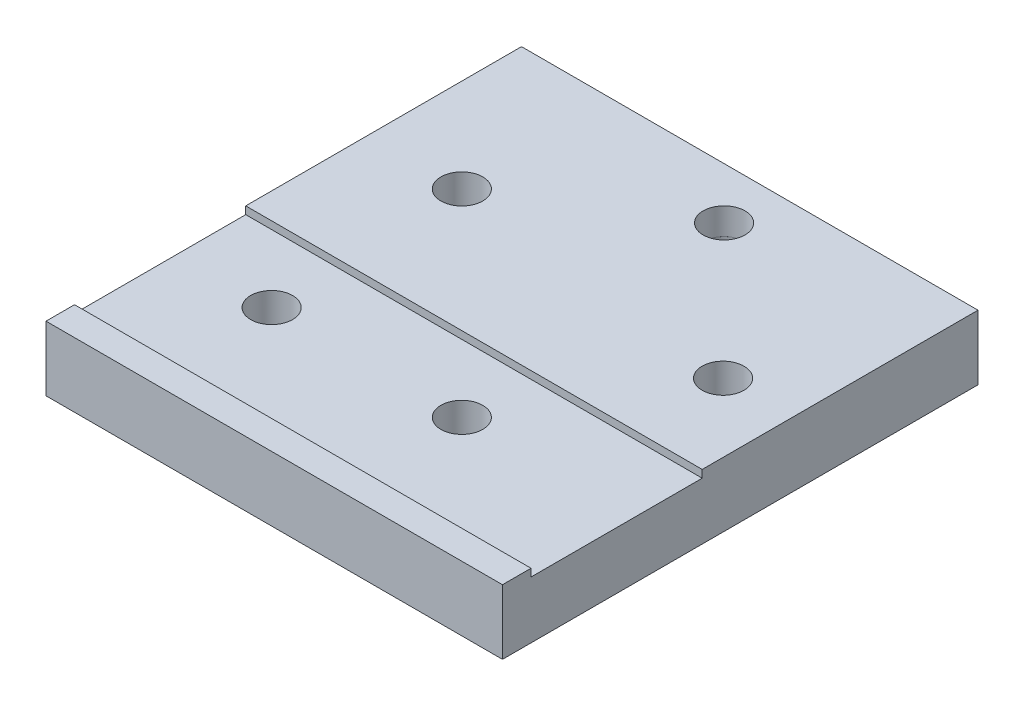
SolidWorks part; units mm, degrees
ref_plane "Front Plane" through (0, 0, 0) normal (0, 0, 1) x (1, 0, 0)
ref_plane "Top Plane" through (0, 0, 0) normal (0, 1, 0) x (1, 0, 0)
ref_plane "Right Plane" through (0, 0, 0) normal (1, 0, 0) x (0, 0, -1)
sketch "Sketch1" plane through (0, 0, 0) normal (0, 1, 0) x (1, 0, 0)
  line L1 (-60, -27.5) -> (60, -27.5)
  line L2 (-60, -27.5) -> (-60, 27.5)
  line L3 (-60, 27.5) -> (60, 27.5)
  line L4 (60, -27.5) -> (60, 27.5)
  line L5 (-60, -27.5) -> (60, 27.5) construction
  line L6 (-60, 27.5) -> (60, -27.5) construction
  point P0 (0, 0)
  dimension "D1" = 55
  dimension "D2" = 120
extrude "Boss-Extrude1" add sketch "Sketch1" along normal blind 5
sketch "Sketch2" plane through (0, 5, 0) normal (0, 1, 0) x (1, 0, 0)
  line L0 (60, -27.5) -> (60, 27.5) construction
  line L1 (-60, -27.5) -> (60, -27.5)
  line L2 (-60, -27.5) -> (-60, -20)
  line L3 (-60, -20) -> (60, -20)
  line L4 (60, -27.5) -> (60, -20)
  dimension "D1" = 7.5
extrude "Boss-Extrude2" add sketch "Sketch2" along normal blind 20
sketch "Sketch3" plane through (0, 5, 0) normal (0, 1, 0) x (1, 0, 0)
  line L0 (-60, 27.5) -> (-60, -20) construction
  line L1 (60, 27.5) -> (-60, 27.5)
  line L2 (60, 27.5) -> (60, 25)
  line L3 (60, 25) -> (-60, 25)
  line L4 (-60, 27.5) -> (-60, 25)
  dimension "D1" = 2.5
extrude "Boss-Extrude4" add sketch "Sketch3" along normal blind 20
sketch "Sketch8" plane through (-60, 0, 0) normal (-1, 0, 0) x (0, 0, 1)
  line L0 (-27.5, 0) -> (-27.5, 25)
  line L1 (-27.5, 25) -> (-25, 25)
  line L2 (-25, 25) -> (-25, 5)
  line L3 (-25, 5) -> (20, 5)
  line L4 (20, 5) -> (20, 25)
  line L5 (20, 25) -> (27.5, 25)
  line L6 (27.5, 25) -> (27.5, 0)
  line L7 (27.5, 0) -> (-27.5, 0)
extrude "Boss-Extrude5" add sketch "Sketch8" along normal blind 190
sketch "Sketch9" plane through (0, 0, -27.5) normal (0, 0, -1) x (-1, 0, 0)
  line L0 (-60, 0) -> (-60, 25)
  line L1 (-60, 25) -> (250, 25)
  line L2 (250, 25) -> (250, 0)
  line L3 (250, 0) -> (-60, 0)
extrude "Boss-Extrude6" add sketch "Sketch9" along normal blind 70
sketch "Sketch14" plane through (0, 0, 0) normal (0, -1, 0) x (-1, 0, 0)
  circle A0 centre (225.4453, 7.2552) radius 5.5
  circle A1 centre (175.4453, 7.2552) radius 5.5
  circle A2 centre (225.4453, 57.2552) radius 5.5
  circle A3 centre (148.0182, 48.5) radius 5.5
  circle A4 centre (183.2409, 83.9875) radius 5.5
  dimension "D1" = 11
  dimension "D3" = 11
  dimension "D5" = 11
  dimension "D6" = 11
  dimension "D8" = 11
  dimension "D2" = 50
  dimension "D4" = 50
  dimension "D7" = 50
extrude "Cut-Extrude5" cut sketch "Sketch14" against normal blind 153
sketch "Sketch15" plane through (60, 0, 0) normal (1, 0, 0) x (0, 0, -1)
  line L1 (-27.5, 25) -> (97.5, 25)
  line L2 (-27.5, 25) -> (-27.5, 0)
  line L3 (-27.5, 0) -> (97.5, 0)
  line L4 (97.5, 25) -> (97.5, 0)
extrude "Cut-Extrude6" cut sketch "Sketch15" against normal blind 190
sketch "Sketch16" plane through (0, 0, 0) normal (0, -1, 0) x (-1, 0, 0)
  line L1 (130, -27.5) -> (250, -27.5)
  line L2 (130, -27.5) -> (130, 97.5)
  line L3 (130, 97.5) -> (250, 97.5)
  line L4 (250, -27.5) -> (250, 97.5)
extrude "Boss-Extrude8" add sketch "Sketch16" along normal blind 10
sketch "Sketch17" plane through (0, 25, 0) normal (0, 1, 0) x (1, 0, 0)
  line L1 (-250, 97.5) -> (-130, 97.5)
  line L2 (-250, 97.5) -> (-250, -27.5)
  line L3 (-250, -27.5) -> (-130, -27.5)
  line L4 (-130, 97.5) -> (-130, -27.5)
extrude "Cut-Extrude7" cut sketch "Sketch17" against normal blind 18
sketch "Sketch18" plane through (0, 7, 0) normal (0, 1, 0) x (1, 0, 0)
  circle A0 centre (-148.0182, 48.5) radius 5.5
extrude "Cut-Extrude8" cut sketch "Sketch18" against normal blind 18
sketch "Sketch19" plane through (0, 7, 0) normal (0, 1, 0) x (1, 0, 0)
  circle A0 centre (-148.0182, 48.5) radius 5.5
sketch "Sketch20" plane through (0, 7, 0) normal (0, 1, 0) x (1, 0, 0)
  circle A0 centre (-183.2409, 83.9875) radius 5.4839
  circle A1 centre (-225.4453, 57.2552) radius 5.5
  point P6 (0, 0)
extrude "Cut-Extrude9" cut sketch "Sketch20" against normal blind 47
sketch "Sketch21" plane through (0, 5, 0) normal (0, 1, 0) x (1, 0, 0)
  circle A0 centre (-225.4453, 7.2552) radius 5.5
extrude "Cut-Extrude10" cut sketch "Sketch21" against normal blind 47
sketch "Sketch22" plane through (0, 5, 0) normal (0, 1, 0) x (1, 0, 0)
  circle A0 centre (-175.4453, 7.2552) radius 5.5
extrude "Cut-Extrude11" cut sketch "Sketch22" against normal blind 47
